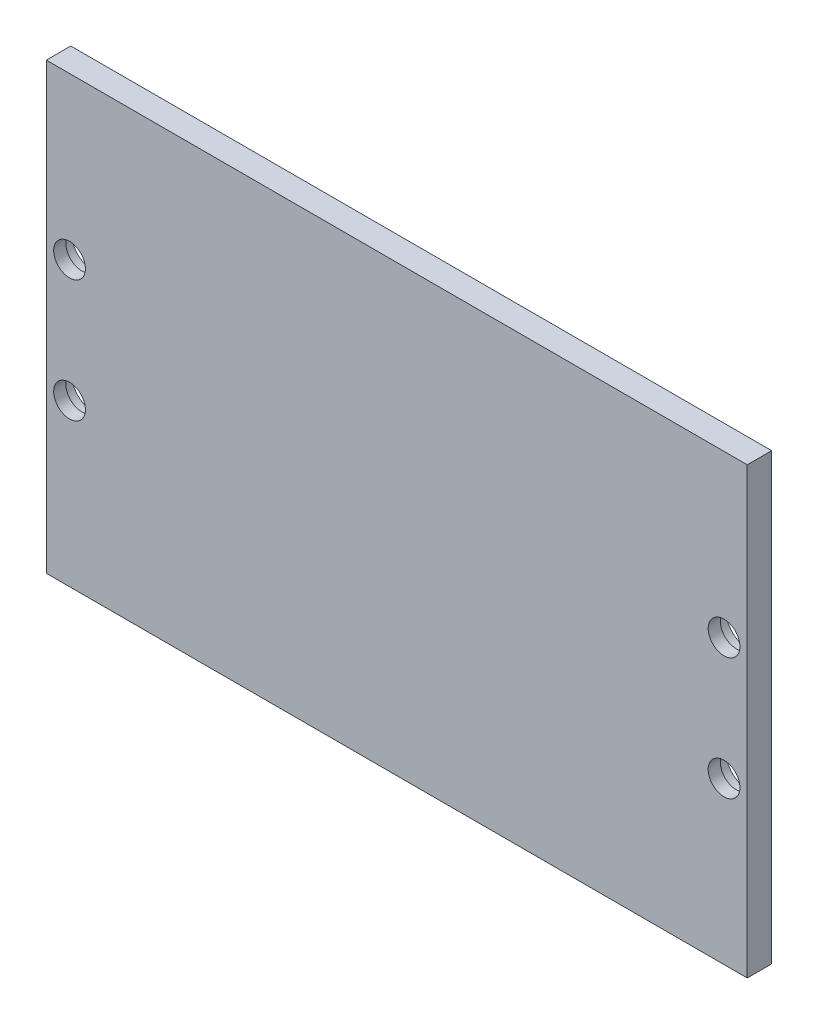
SolidWorks part; units mm, degrees
ref_plane "前基準面" through (0, 0, 0) normal (0, 0, 1) x (1, 0, 0)
ref_plane "上基準面" through (0, 0, 0) normal (0, 1, 0) x (1, 0, 0)
ref_plane "右基準面" through (0, 0, 0) normal (1, 0, 0) x (0, 0, -1)
sketch "草圖1" plane through (0, 0, 0) normal (0, 0, 1) x (1, 0, 0)
  line L1 (26.5206, 22.7774) -> (-2.1794, 22.7774)
  line L2 (26.5206, 22.7774) -> (26.5206, 40.9774)
  line L3 (26.5206, 40.9774) -> (-2.1794, 40.9774)
  line L4 (-2.1794, 22.7774) -> (-2.1794, 40.9774)
  point P4 (-2.1113, 40.7927)
  point P5 (-2.1742, 40.9893)
  point P6 (26.4981, 40.9537)
  point P7 (26.5206, 40.9774)
  point P8 (-2.2199, 22.5655)
  point P9 (-2.1416, 41.02)
  point P10 (-2.1382, 41.0209)
  point P11 (-2.1793, 41.0288)
  point P12 (-2.1793, 22.571)
  point P13 (0, 0)
  point P14 (26.5206, 22.5345)
  point P15 (26.5206, 40.9774)
  point P16 (-2.177, 22.5652)
  point P17 (-2.1705, 22.576)
  point P18 (-2.1794, 22.571)
  dimension "D1" = 28.7
  dimension "D2" = 18.2
extrude "填料-伸長1" add sketch "草圖1" along normal blind 1
sketch "草圖2" plane through (0, 0, 1) normal (0, 0, 1) x (1, 0, 0)
  line L0 (26.5206, 40.9774) -> (-2.1794, 40.9774) construction
  line L1 (-2.1794, 40.9774) -> (-2.1794, 22.7774) construction
  line L2 (-1.2294, 34.3774) -> (-2.1794, 34.3774) construction
  line L3 (-1.2294, 34.3774) -> (-1.2294, 40.9774) construction
  line L4 (-1.2294, 29.3774) -> (-2.1794, 29.3774) construction
  line L5 (-1.2294, 29.3774) -> (-1.2294, 22.7774) construction
  line L6 (-2.1794, 22.7774) -> (26.5206, 22.7774) construction
  line L7 (25.5706, 34.3774) -> (26.5206, 34.3774) construction
  line L8 (25.5706, 34.3774) -> (25.5706, 40.9774) construction
  line L9 (26.5206, 22.7774) -> (26.5206, 40.9774) construction
  line L10 (25.5706, 29.3774) -> (26.5206, 29.3774) construction
  line L11 (25.5706, 29.3774) -> (25.5706, 22.7774) construction
  circle A0 centre (25.5706, 34.3774) radius 0.925
  circle A1 centre (25.5706, 29.3774) radius 0.925
  circle A2 centre (-1.2294, 34.3774) radius 0.925
  circle A3 centre (-1.2294, 29.3774) radius 0.925
  point P8 (-1.2236, 22.5774)
  point P17 (-2.1794, 28.7185)
  point P18 (-1.2294, 28.7185)
  point P21 (24.8925, 40.9774)
  point P24 (26.5206, 34.3019)
  point P27 (24.7827, 34.3019)
  point P28 (24.9199, 22.5774)
  point P31 (26.5206, 28.7185)
  point P32 (25.4414, 28.7185)
  dimension "D3" = 1.85
  dimension "D1" = 6.6
  dimension "D2" = 0.95
extrude "除料-伸長1" cut sketch "草圖2" against normal through all
sketch "草圖3" plane through (0, 0, 1) normal (0, 0, -1) x (-1, 0, 0)
  line L0 (-26.5206, 40.9774) -> (2.1794, 40.9774) construction
  line L1 (2.1794, 40.9774) -> (2.1794, 22.7774) construction
  line L2 (-26.5206, 31.8774) -> (2.1794, 31.8774) construction
  line L3 (-26.5206, 22.7774) -> (-26.5206, 40.9774) construction
  line L4 (-12.1706, 40.9774) -> (-12.1706, 22.7774) construction
  line L5 (2.1794, 22.7774) -> (-26.5206, 22.7774) construction
  circle A0 centre (1.2294, 34.3774) radius 0.925
  circle A1 centre (1.2294, 34.3774) radius 0.65
  circle A2 centre (1.2294, 29.3774) radius 0.65
  circle A3 centre (1.2294, 29.3774) radius 0.925
  circle A4 centre (-25.5706, 29.3774) radius 0.65
  circle A5 centre (-25.5706, 29.3774) radius 0.925
  circle A6 centre (-25.5706, 34.3774) radius 0.65
  circle A7 centre (-25.5706, 34.3774) radius 0.925
  dimension "D1" = 1.3
  dimension "D2" = 1.85
  dimension "D3" = 6.6
  dimension "D4" = 0.95
extrude "填料-伸長2" add sketch "草圖3" along normal blind 0.5
